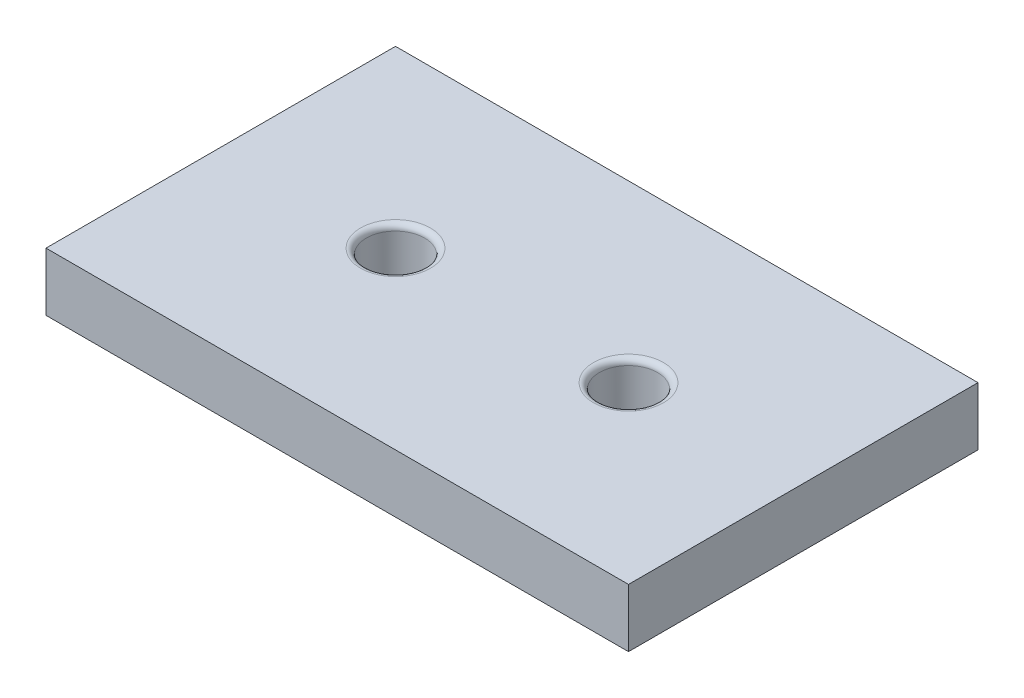
SolidWorks part; units mm, degrees
ref_plane "前视基准面" through (0, 0, 0) normal (0, 0, 1) x (1, 0, 0)
ref_plane "上视基准面" through (0, 0, 0) normal (0, 1, 0) x (1, 0, 0)
ref_plane "右视基准面" through (0, 0, 0) normal (1, 0, 0) x (0, 0, -1)
other "Configuration Table"
sketch "草图1" plane through (0, 0, 0) normal (0, 1, 0) x (1, 0, 0)
  line L1 (-50, -30) -> (50, -30)
  line L2 (-50, -30) -> (-50, 30)
  line L3 (-50, 30) -> (50, 30)
  line L4 (50, -30) -> (50, 30)
  line L5 (0, 30) -> (0, -30) construction
  line L6 (-50, 0) -> (50, 0) construction
  point P0 (0, 0)
extrude "凸台-拉伸1" add sketch "草图1" along normal blind 10
sketch "草图2" plane through (0, 0, 0) normal (0, 1, 0) x (1, 0, 0)
  circle A0 centre (-20, 0) radius 5
extrude "切除-拉伸1" cut sketch "草图2" along normal blind 20
sketch "草图3" plane through (0, 0, 0) normal (0, 1, 0) x (1, 0, 0)
  circle A0 centre (20, 0) radius 5
extrude "切除-拉伸2" cut sketch "草图3" along normal blind 20
fillet "圆角1" radius 1 2 edges at (20, 10, -5) (-20, 10, -5)
sketch "草图4" plane through (0, 0, 0) normal (0, 1, 0) x (1, 0, 0)
  line L0 (-10, -20) -> (10, -20)
